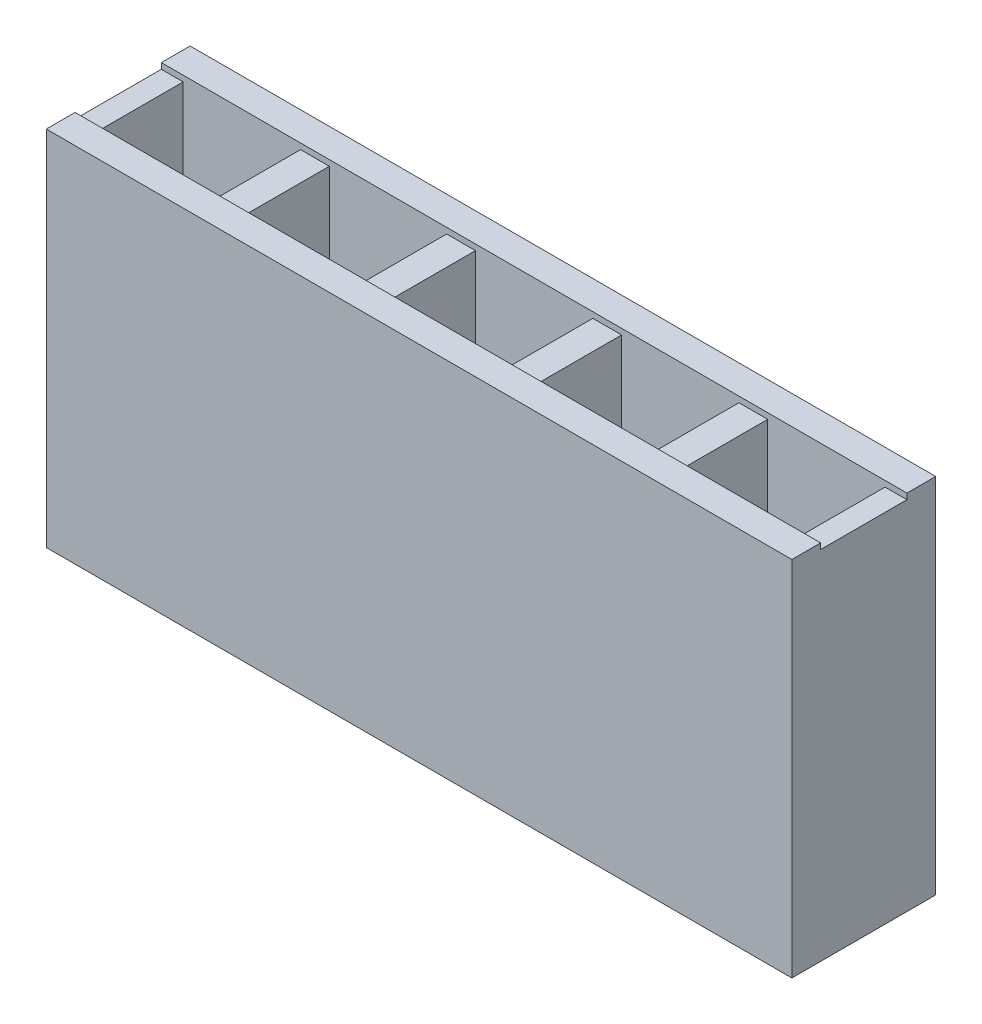
SolidWorks part; units mm, degrees
ref_plane "Front Plane" through (0, 0, 0) normal (0, 0, 1) x (1, 0, 0)
ref_plane "Top Plane" through (0, 0, 0) normal (0, 1, 0) x (1, 0, 0)
ref_plane "Right Plane" through (0, 0, 0) normal (1, 0, 0) x (0, 0, -1)
sketch "Sketch1" plane through (0, 0, 0) normal (0, 1, 0) x (1, 0, 0)
  line L1 (-6.48, -1.25) -> (6.48, -1.25)
  line L2 (-6.48, -1.25) -> (-6.48, 1.25)
  line L3 (-6.48, 1.25) -> (6.48, 1.25)
  line L4 (6.48, -1.25) -> (6.48, 1.25)
  line L5 (-6.48, -1.25) -> (6.48, 1.25) construction
  line L6 (-6.48, 1.25) -> (6.48, -1.25) construction
  point P0 (0, 0)
  dimension "D1" = 2.5
  dimension "D2" = 12.96
extrude "Boss-Extrude1" add sketch "Sketch1" along normal blind 6.2
sketch "Sketch2" plane through (0, 6.2, 0) normal (0, 1, 0) x (1, 0, 0)
  line L0 (-6.48, 1.25) -> (-6.48, -1.25) construction
  line L1 (-6.1, -0.75) -> (-4.06, -0.75)
  line L2 (-6.1, -0.75) -> (-6.1, 0.75)
  line L3 (-6.1, 0.75) -> (-4.06, 0.75)
  line L4 (-4.06, -0.75) -> (-4.06, 0.75)
  line L5 (-6.1, -0.75) -> (-4.06, 0.75) construction
  line L6 (-6.1, 0.75) -> (-4.06, -0.75) construction
  point P0 (-5.08, 0)
  dimension "D1" = 1.4
  dimension "D2" = 2.04
  dimension "D3" = 1.5
extrude "Cut-Extrude1" cut sketch "Sketch2" against normal blind 5.75
sketch "Sketch3" plane through (0, 0, 0) normal (0, -1, 0) x (1, 0, 0)
  line L1 (-5.88, -0.8) -> (-4.28, -0.8)
  line L2 (-5.88, -0.8) -> (-5.88, 0.8)
  line L3 (-5.88, 0.8) -> (-4.28, 0.8)
  line L4 (-4.28, -0.8) -> (-4.28, 0.8)
  line L5 (-5.88, -0.8) -> (-4.28, 0.8) construction
  line L6 (-5.88, 0.8) -> (-4.28, -0.8) construction
  line L7 (-6.48, 1.25) -> (6.48, 1.25) construction
  line L8 (-6.48, -1.25) -> (-6.48, 1.25) construction
  point P0 (-5.08, 0)
  dimension "D1" = 1.6
  dimension "D2" = 1.4
  dimension "D3" = 0.45
extrude "Cut-Extrude2" cut sketch "Sketch3" against normal up to next (0.45 mm away) draft 45
pattern_linear "LPattern1" count 5 spacing 2.54 along (1, 0, 0) of "Cut-Extrude1", "Cut-Extrude2"
sketch "Sketch4" plane through (0, 6.2, 0) normal (0, 1, 0) x (1, 0, 0)
  line L0 (-6.48, 1.25) -> (-6.48, -1.25) construction
  line L1 (6.48, 0.75) -> (-6.48, 0.75)
  line L2 (6.48, 0.75) -> (6.48, 1.25)
  line L3 (6.48, 1.25) -> (-6.48, 1.25)
  line L4 (-6.48, 0.75) -> (-6.48, 1.25)
  line L8 (6.48, -1.25) -> (6.48, 1.25) construction
  line L9 (6.48, 1.25) -> (-6.48, 1.25) construction
extrude "Boss-Extrude2" add sketch "Sketch4" along normal blind 0.1
mirror "Mirror1" about plane through (0, 0, 0) normal (0, 0, 1) of "Boss-Extrude2"
